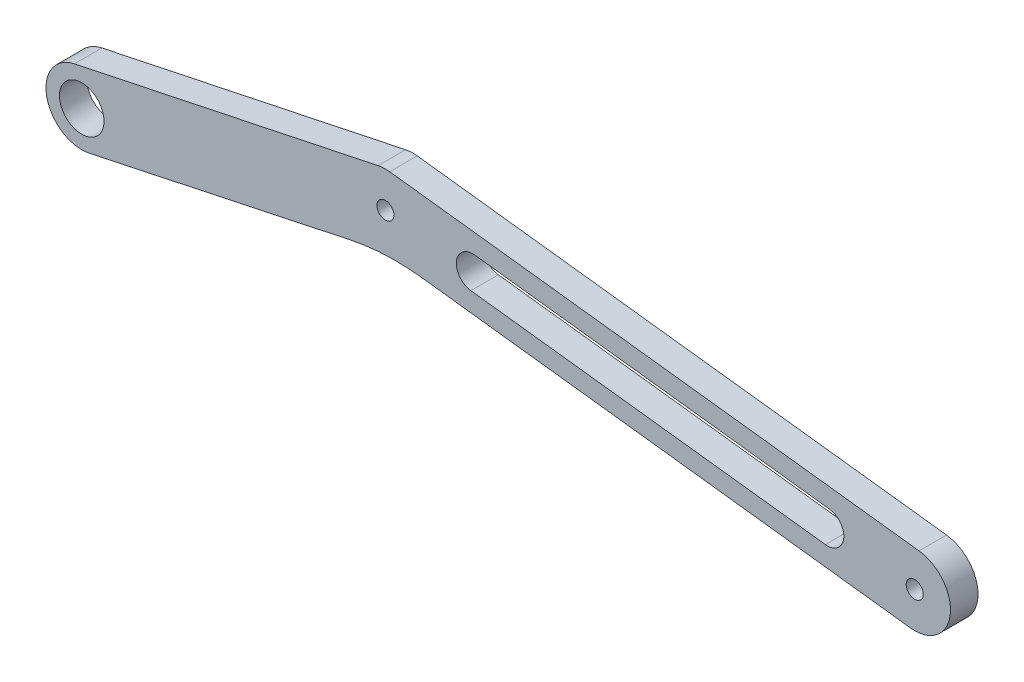
SolidWorks part; units mm, degrees
material "Hexcel AS4C (3000 丝)"
ref_plane "前视基准面" through (0, 0, 0) normal (0, 0, 1) x (1, 0, 0)
ref_plane "上视基准面" through (0, 0, 0) normal (0, 1, 0) x (1, 0, 0)
ref_plane "右视基准面" through (0, 0, 0) normal (1, 0, 0) x (0, 0, -1)
sketch "草图1" plane through (0, 0, 0) normal (0, 0, 1) x (1, 0, 0)
  line L0 (1.3502, -6.3582) -> (55.1991, 5.0768)
  line L1 (-1.3342, 6.3616) -> (53.8649, 17.9384)
  line L2 (55.9757, 18.0302) -> (152.1766, 6.4534)
  line L3 (55.1991, 5.0768) -> (150.6203, -6.4531)
  circle A0 centre (0, 0) radius 4.05
  circle A1 centre (151.4, 0) radius 1.55
  circle A2 centre (55.1991, 11.5768) radius 1.55
  circle A3 centre (0, 0) radius 6.5
  circle A4 centre (55.1991, 11.5768) radius 6.5
  circle A5 centre (151.4, 0) radius 6.5
  dimension "D1" = 8.1
  dimension "D2" = 56.4
  dimension "D3" = 96.895
  dimension "D4" = 151.4
  dimension "D5" = 13
  dimension "D6" = 3.1
  dimension "D7" = 3.1
extrude "凸台-拉伸1" add sketch "草图1" along normal blind 5 contours A3 A0 | A4 L1 A3 L0 | A4 A2 | A5 L2 A4 L3 | A5 A1
fillet "圆角1" radius 40 1 edges at (55.1991, 5.0768, 2.5)
sketch "草图2" plane through (0, 0, 5) normal (0, 0, 1) x (1, 0, 0)
  line L0 (55.1991, 11.5768) -> (151.4, 0) construction
  line L1 (71.0845, 9.6652) -> (135.5146, 1.9116) construction
  line L2 (71.4429, 12.6437) -> (135.873, 4.8902)
  line L3 (70.726, 6.6867) -> (135.1562, -1.0669)
  arc A0 (71.4429, 12.6437) -> (70.726, 6.6867) centre (71.0845, 9.6652) ccw
  arc A1 (135.1562, -1.0669) -> (135.873, 4.8902) centre (135.5146, 1.9116) ccw
  point P6 (103.2995, 5.7884)
  dimension "D3" = 3
  dimension "D1" = 16
  dimension "D2" = 16
extrude "切除-拉伸1" cut sketch "草图2" against normal through all
